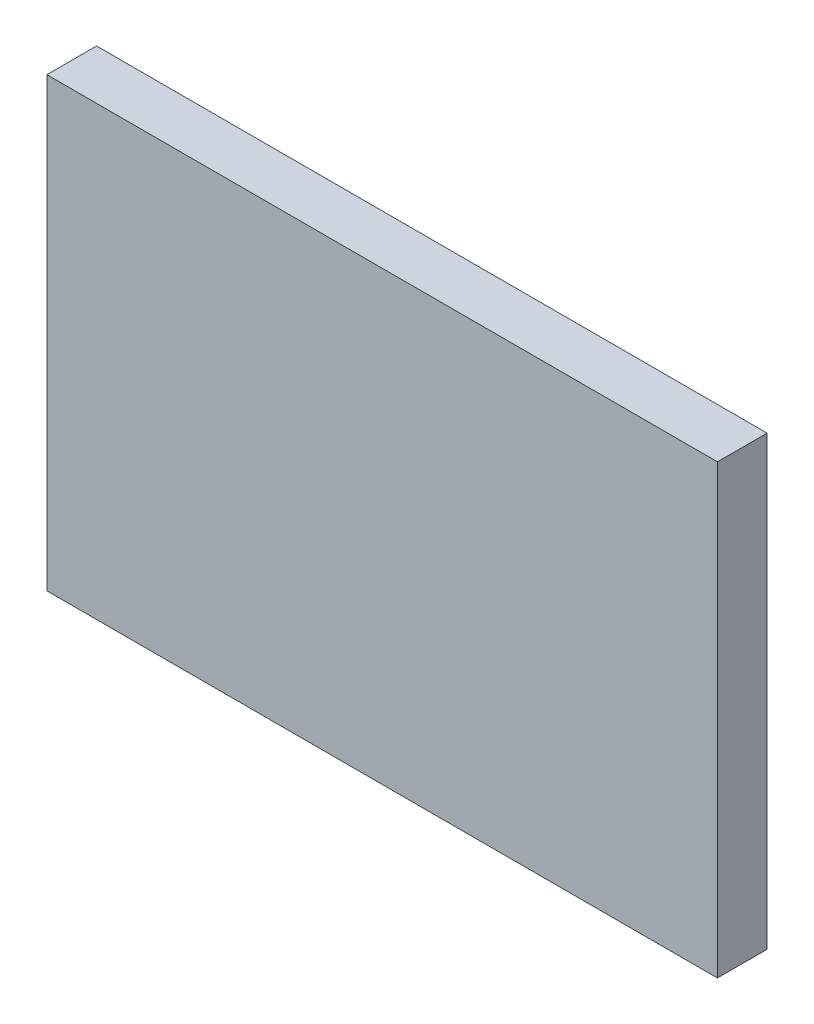
SolidWorks part; units mm, degrees
ref_plane "Front Plane" through (0, 0, 0) normal (0, 0, 1) x (1, 0, 0)
ref_plane "Top Plane" through (0, 0, 0) normal (0, 1, 0) x (1, 0, 0)
ref_plane "Right Plane" through (0, 0, 0) normal (1, 0, 0) x (0, 0, -1)
sketch "Sketch1" plane through (0, 0, 0) normal (0, 0, 1) x (1, 0, 0)
  line L1 (0, 0) -> (171.45, 0)
  line L2 (0, 0) -> (0, 114.3)
  line L3 (0, 114.3) -> (171.45, 114.3)
  line L4 (171.45, 0) -> (171.45, 114.3)
  dimension "D1" = 114.3
  dimension "D2" = 171.45
extrude "Boss-Extrude1" add sketch "Sketch1" along normal blind 12.7
